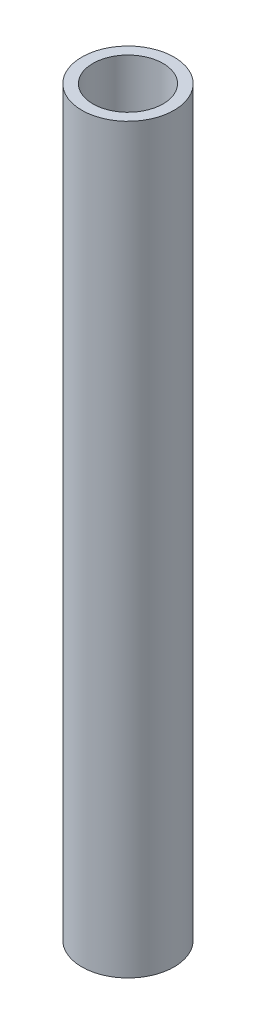
SolidWorks part; units mm, degrees
material "Malleable Cast Iron"
ref_plane "Front Plane" through (0, 0, 0) normal (0, 0, 1) x (1, 0, 0)
ref_plane "Top Plane" through (0, 0, 0) normal (0, 1, 0) x (1, 0, 0)
ref_plane "Right Plane" through (0, 0, 0) normal (1, 0, 0) x (0, 0, -1)
sketch "Sketch1" plane through (0, 0, 0) normal (0, 1, 0) x (1, 0, 0)
  circle A0 centre (0, 0) radius 1.75
  circle A1 centre (0, 0) radius 2.3
  dimension "D1" = 3.5
  dimension "D2" = 4.6
extrude "Boss-Extrude1" add sketch "Sketch1" along normal mid plane 37
